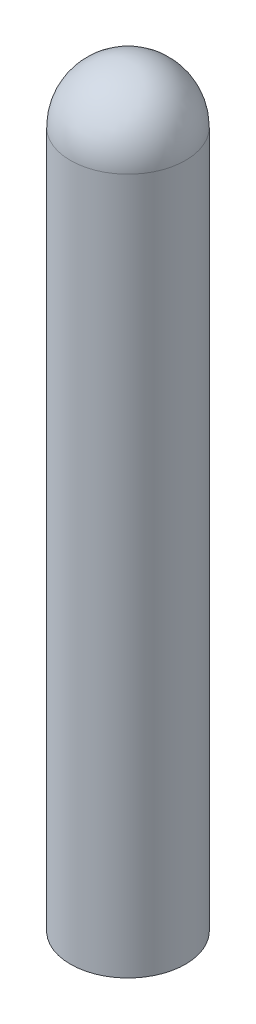
SolidWorks part; units mm, degrees
ref_plane "Front Plane" through (0, 0, 0) normal (0, 0, 1) x (1, 0, 0)
ref_plane "Top Plane" through (0, 0, 0) normal (0, 1, 0) x (1, 0, 0)
ref_plane "Right Plane" through (0, 0, 0) normal (1, 0, 0) x (0, 0, -1)
sketch "Sketch1" plane through (0, 0, 0) normal (0, 1, 0) x (1, 0, 0)
  circle A0 centre (0, 0) radius 7.85
  circle A1 centre (0, 0) radius 6.9
extrude "Boss-Extrude1" add sketch "Sketch1" along normal blind 95
sketch "Sketch2" plane through (0, 95, 0) normal (0, 1, 0) x (1, 0, 0)
  line L0 (0, 7.85) -> (0, -7.85)
  line L1 (0, 7.85) -> (0, 6.9)
  line L2 (0, -7.85) -> (0, -6.9)
  arc A0 (0, 7.85) -> (0, -7.85) centre (0, 0) ccw
  arc A1 (0, 6.9) -> (0, -6.9) centre (0, 0) ccw
revolve "Revolve2" add sketch "Sketch2" angle 360 about L0
